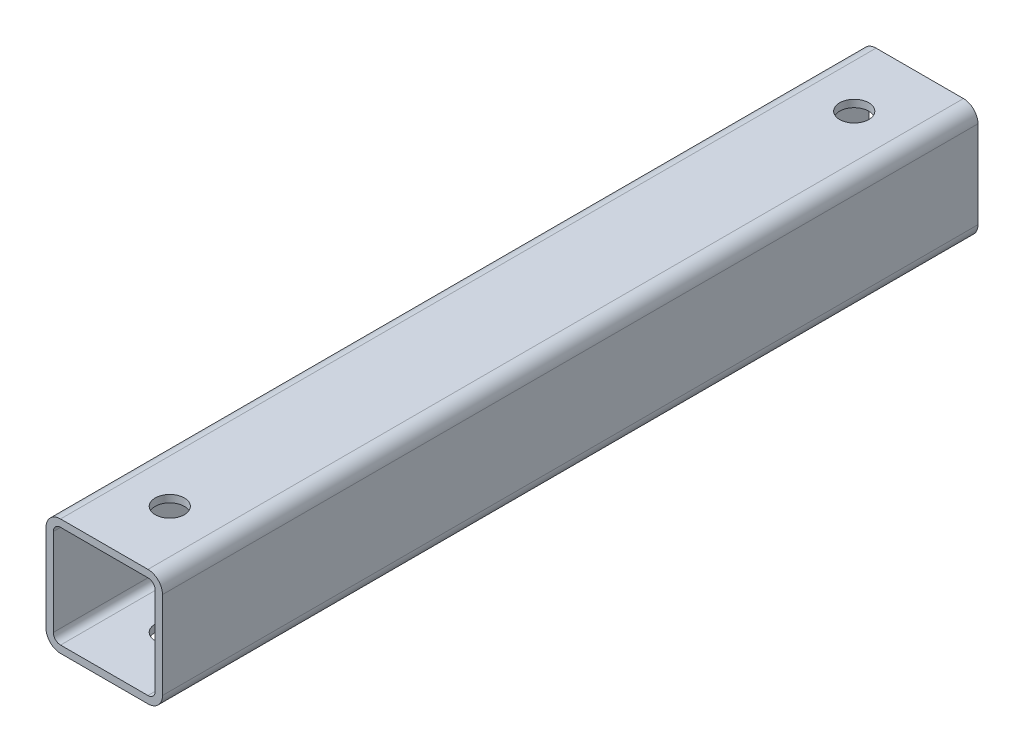
SolidWorks part; units mm, degrees
material "ASTM A36 Steel"
ref_plane "Front Plane" through (0, 0, 0) normal (0, 0, 1) x (1, 0, 0)
ref_plane "Top Plane" through (0, 0, 0) normal (0, 1, 0) x (1, 0, 0)
ref_plane "Right Plane" through (0, 0, 0) normal (1, 0, 0) x (0, 0, -1)
sketch "Sketch1" plane through (0, 0, 0) normal (0, 0, 1) x (1, 0, 0)
  line L0 (-38.1, 44.45) -> (38.1, 44.45)
  line L1 (-38.1, -50.8) -> (38.1, -50.8)
  line L2 (-50.8, -38.1) -> (-50.8, 38.1)
  line L3 (-38.1, 50.8) -> (38.1, 50.8)
  line L4 (50.8, -38.1) -> (50.8, 38.1)
  line L5 (-50.8, -50.8) -> (50.8, 50.8) construction
  line L6 (-50.8, 50.8) -> (50.8, -50.8) construction
  line L7 (44.45, -38.1) -> (44.45, 38.1)
  line L8 (-38.1, -44.45) -> (38.1, -44.45)
  line L9 (-44.45, -38.1) -> (-44.45, 38.1)
  arc A0 (38.1, -50.8) -> (50.8, -38.1) centre (38.1, -38.1) ccw
  arc A1 (-50.8, 38.1) -> (-38.1, 50.8) centre (-38.1, 38.1) cw
  arc A2 (-38.1, -50.8) -> (-50.8, -38.1) centre (-38.1, -38.1) cw
  arc A3 (38.1, 50.8) -> (50.8, 38.1) centre (38.1, 38.1) cw
  arc A4 (38.1, 44.45) -> (44.45, 38.1) centre (38.1, 38.1) cw
  arc A5 (38.1, -44.45) -> (44.45, -38.1) centre (38.1, -38.1) ccw
  arc A6 (-38.1, -44.45) -> (-44.45, -38.1) centre (-38.1, -38.1) cw
  arc A7 (-44.45, 38.1) -> (-38.1, 44.45) centre (-38.1, 38.1) cw
  point P0 (0, 0)
  dimension "D3" = 12.7
  dimension "D1" = 101.6
  dimension "D2" = 101.6
  dimension "D4" = 6.35
extrude "Boss-Extrude1" add sketch "Sketch1" along normal mid plane 711.2
sketch "Sketch2" plane through (0, 50.8, 0) normal (0, 1, 0) x (1, 0, 0)
  line L0 (38.1, -355.6) -> (-38.1, -355.6) construction
  line L1 (50.8, -355.6) -> (50.8, 355.6) construction
  line L2 (-55.88, 0) -> (55.88, 0) construction
  circle A1 centre (0, -298.45) radius 12.7
  circle A2 centre (0, 298.45) radius 12.7
  dimension "D1" = 25.4
  dimension "D2" = 57.15
  dimension "D3" = 50.8
extrude "Cut-Extrude1" cut sketch "Sketch2" against normal through all
equation "\"PRIMER_USAGE\"= ( \"SW-SurfaceArea\" / 144 ) / 135"
equation "\"WET_PAINT_USAGE\"= ( \"SW-SurfaceArea\" / 144 ) / 125"
equation "\"POWDERCOAT_USAGE\"= ( \"SW-SurfaceArea\" / 144 ) / 29.79"
equation "\"DECKOVER_USAGE\"= ( \"SW-SurfaceArea\" / 144 ) / 75"
equation "\"SW_NON-SKID\"= ( \"SW-SurfaceArea\" / 144 ) / 165"
equation "\"TYPE_1_ANODIZATING\"= ( \"SW-SurfaceArea\" * 0.0001 )"
equation "\"TYPE_2_ANODIZING\"= ( \"SW-SurfaceArea\" * 0.0005 )"
equation "\"TYPE_3_ANODIZING-HARDCOAT\"= ( \"SW-SurfaceArea\" * 0.003 )"
